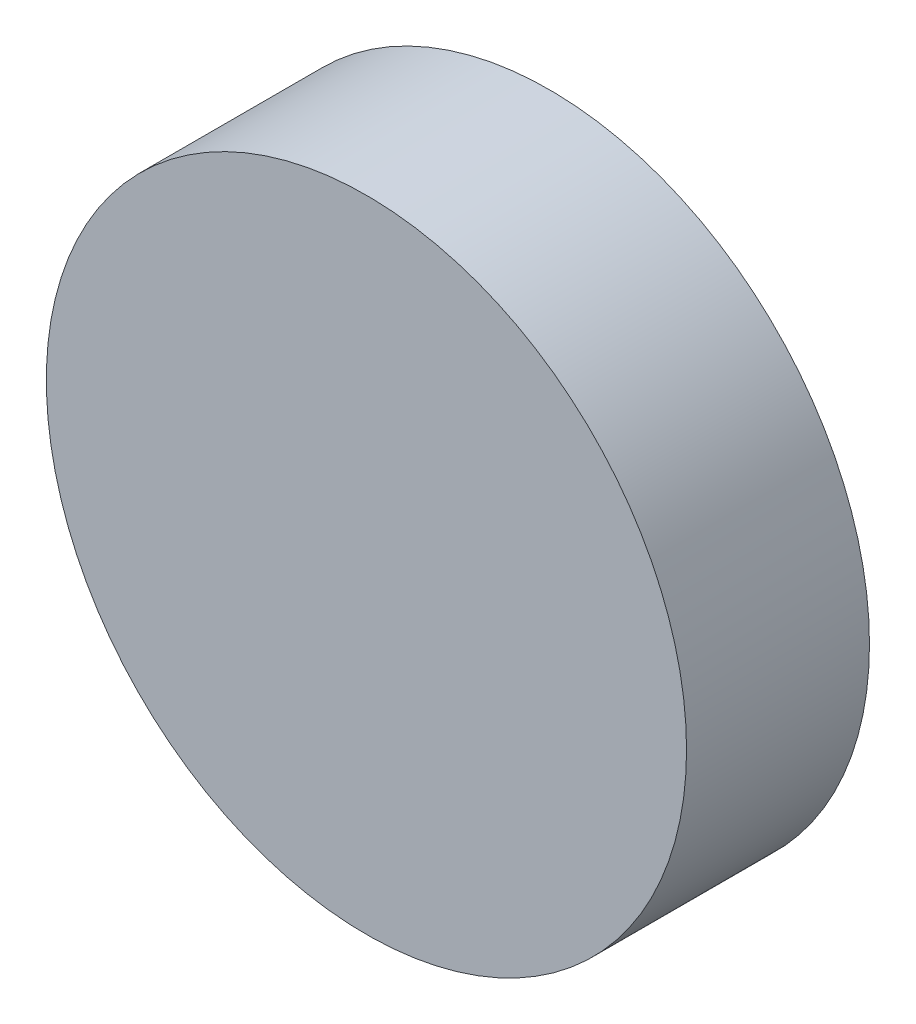
SolidWorks part; units mm, degrees
ref_plane "前视基准面" through (0, 0, 0) normal (0, 0, 1) x (1, 0, 0)
ref_plane "上视基准面" through (0, 0, 0) normal (0, 1, 0) x (1, 0, 0)
ref_plane "右视基准面" through (0, 0, 0) normal (1, 0, 0) x (0, 0, -1)
sketch "草图1" plane through (0, 0, 0) normal (0, 0, 1) x (1, 0, 0)
  circle A0 centre (0, 0) radius 35
  dimension "D1" = 70
extrude "凸台-拉伸1" add sketch "草图1" along normal blind 20
